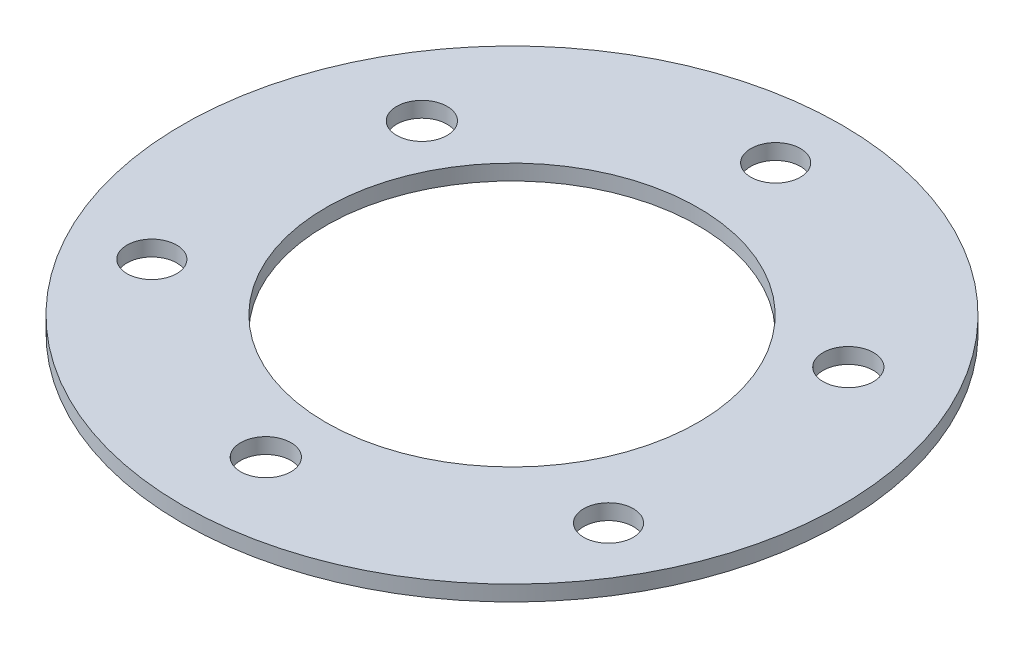
SolidWorks part; units mm, degrees
ref_plane "Front Plane" through (0, 0, 0) normal (0, 0, 1) x (1, 0, 0)
ref_plane "Top Plane" through (0, 0, 0) normal (0, 1, 0) x (1, 0, 0)
ref_plane "Right Plane" through (0, 0, 0) normal (1, 0, 0) x (0, 0, -1)
sketch "Sketch1" plane through (0, 0, 0) normal (0, 1, 0) x (1, 0, 0)
  circle A0 centre (0, 0) radius 42.5
  circle A1 centre (0, 0) radius 24
  dimension "D1" = 85
  dimension "D2" = 48
extrude "Boss-Extrude1" add sketch "Sketch1" along normal blind 2
sketch "Sketch3" plane through (0, 2, 0) normal (0, 1, 0) x (1, 0, 0)
  circle A0 centre (0, 0) radius 34
  circle A1 centre (0, 0) radius 31.75
  circle A2 centre (0, -31.75) radius 3.25
  circle A6 centre (-27.4963, 15.875) radius 3.25
  circle A7 centre (27.4963, 15.875) radius 3.25
  circle A12 centre (0, 34) radius 3.2
  circle A13 centre (29.4449, -17) radius 3.2
  circle A14 centre (-29.4449, -17) radius 3.2
  point P12 (0, 0)
  point P13 (0, 0)
  point P20 (0, 0)
  point P23 (0, 0)
  dimension "D1" = 68
  dimension "D2" = 63.5
  dimension "D3" = 6.5
  dimension "D4" = 6.4
extrude "Cut-Extrude1" cut sketch "Sketch3" against normal blind 2 contours A2 | A13 | A7 | A12 | A6 | A14
